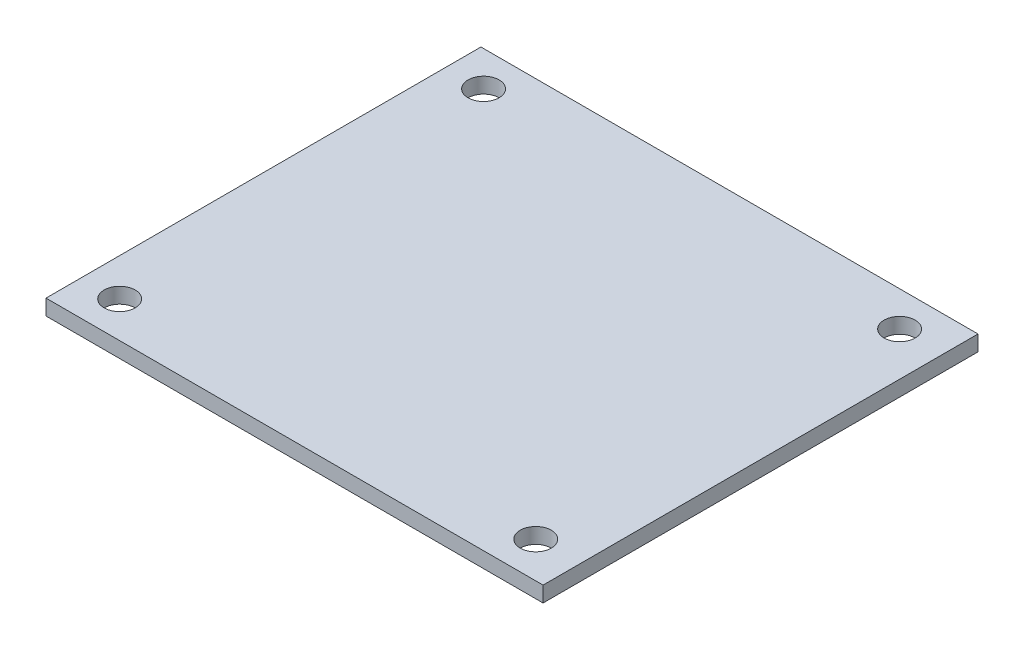
SolidWorks part; units mm, degrees
ref_plane "Front Plane" through (0, 0, 0) normal (0, 0, 1) x (1, 0, 0)
ref_plane "Top Plane" through (0, 0, 0) normal (0, 1, 0) x (1, 0, 0)
ref_plane "Right Plane" through (0, 0, 0) normal (1, 0, 0) x (0, 0, -1)
sketch "Sketch1" plane through (0, 0, 0) normal (0, 1, 0) x (1, 0, 0)
  line L1 (-24, 21) -> (24, 21)
  line L2 (-24, 21) -> (-24, -21)
  line L3 (-24, -21) -> (24, -21)
  line L4 (24, 21) -> (24, -21)
  line L5 (-24, 21) -> (24, -21) construction
  line L6 (-24, -21) -> (24, 21) construction
  point P0 (0, 0)
extrude "Boss-Extrude1" add sketch "Sketch1" along normal blind 1.5
sketch "Sketch2" plane through (0, 1.5, 0) normal (0, 1, 0) x (1, 0, 0)
  circle A0 centre (-20.3717, 17.6272) radius 1.5
  circle A1 centre (19.8058, 17.6272) radius 1.5
  circle A2 centre (19.8058, -17.514) radius 1.5
  circle A3 centre (-20.3717, -17.514) radius 1.5
extrude "Cut-Extrude1" cut sketch "Sketch2" against normal through all
